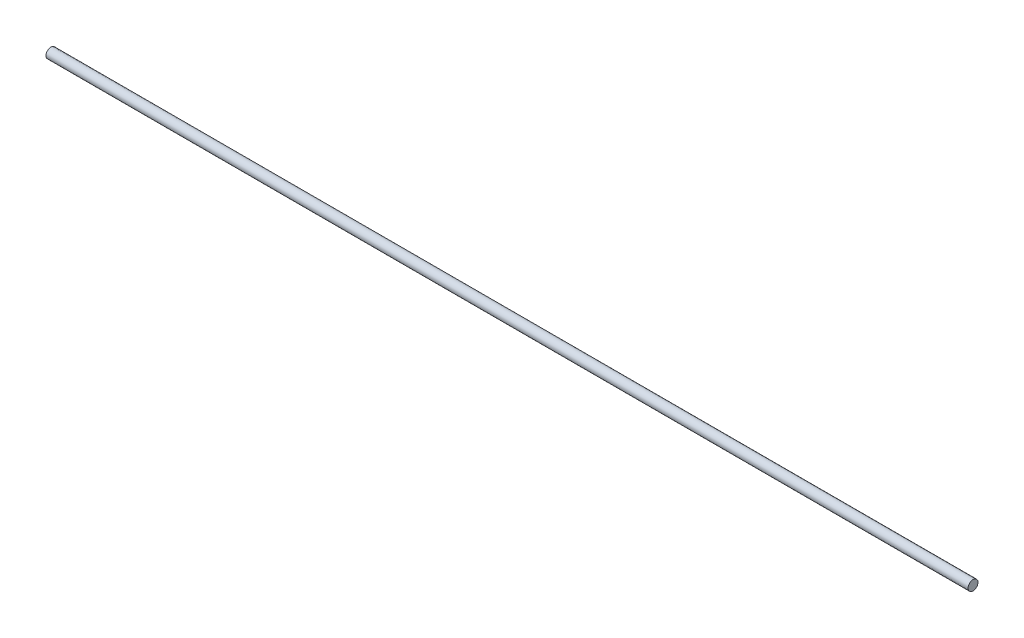
SolidWorks part; units mm, degrees
material "201 Annealed Stainless Steel (SS)"
ref_plane "Front Plane" through (0, 0, 0) normal (0, 0, 1) x (1, 0, 0)
ref_plane "Top Plane" through (0, 0, 0) normal (0, 1, 0) x (1, 0, 0)
ref_plane "Right Plane" through (0, 0, 0) normal (1, 0, 0) x (0, 0, -1)
sketch "Sketch1" plane through (0, 0, 0) normal (1, 0, 0) x (0, 0, -1)
  circle A0 centre (0, 0) radius 4
  dimension "D1" = 8
extrude "Boss-Extrude1" add sketch "Sketch1" along normal blind 746
